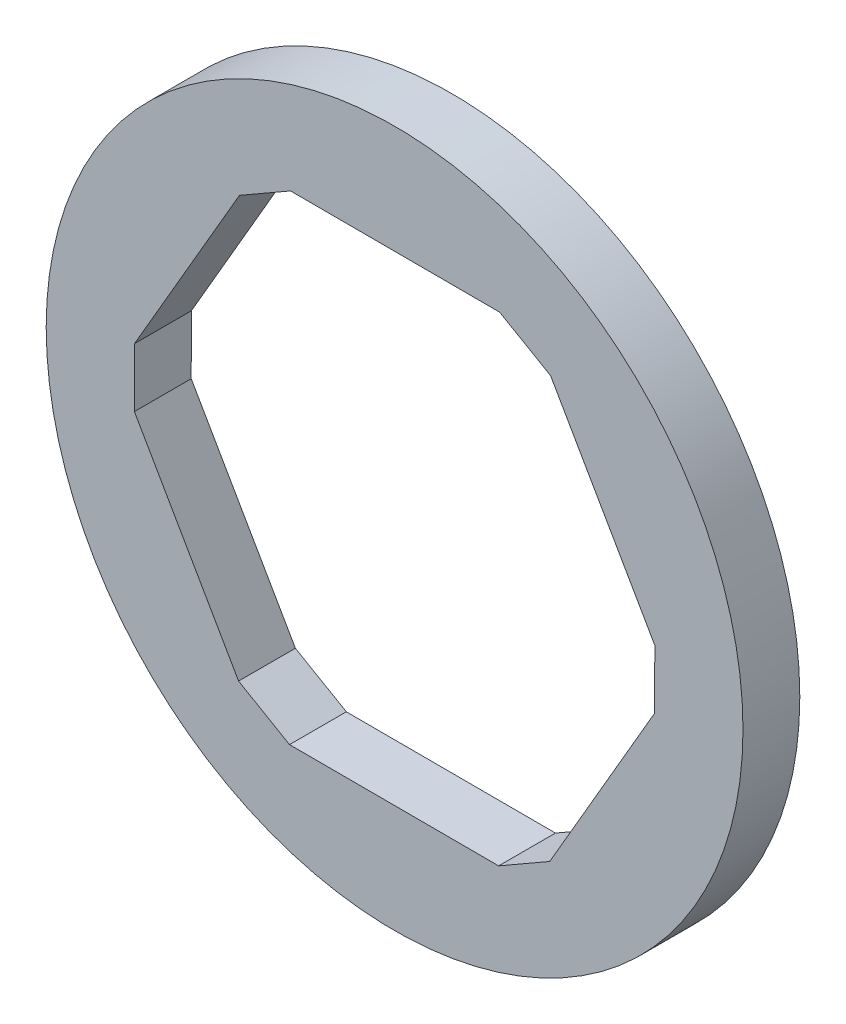
SolidWorks part; units mm, degrees
ref_plane "Front Plane" through (0, 0, 0) normal (0, 0, 1) x (1, 0, 0)
ref_plane "Top Plane" through (0, 0, 0) normal (0, 1, 0) x (1, 0, 0)
ref_plane "Right Plane" through (0, 0, 0) normal (1, 0, 0) x (0, 0, -1)
sketch "Sketch1" plane through (0, 0, 0) normal (0, 0, 1) x (1, 0, 0)
  line L0 (-2.7674, 6.3894) -> (-4.1256, 5.6092)
  line L1 (2.7949, 6.3775) -> (-2.7674, 6.3894)
  line L2 (-4.1256, 5.6092) -> (-6.9171, 0.7981)
  line L3 (-6.9205, -0.7683) -> (-4.1497, -5.5914)
  line L4 (-2.7949, -6.3775) -> (2.7674, -6.3894)
  line L5 (4.1256, -5.6092) -> (6.9171, -0.7981)
  line L6 (6.9205, 0.7683) -> (4.1497, 5.5914)
  line L7 (4.1497, 5.5914) -> (2.7949, 6.3775)
  line L8 (6.9171, -0.7981) -> (6.9205, 0.7683)
  line L9 (2.7674, -6.3894) -> (4.1256, -5.6092)
  line L10 (-4.1497, -5.5914) -> (-2.7949, -6.3775)
  line L11 (-6.9171, 0.7981) -> (-6.9205, -0.7683)
  circle A0 centre (0, 0) radius 9.2668
  circle A1 centre (0, 0) radius 6.3835 construction
  point P4 (3.6992, 6.3755)
  point P5 (-3.6718, 6.3914)
  point P6 (-7.371, 0.0158)
  point P7 (-3.6992, -6.3755)
  point P8 (3.6718, -6.3914)
  point P9 (7.371, -0.0158)
extrude "Boss-Extrude1" add sketch "Sketch1" along normal blind 1.5113
